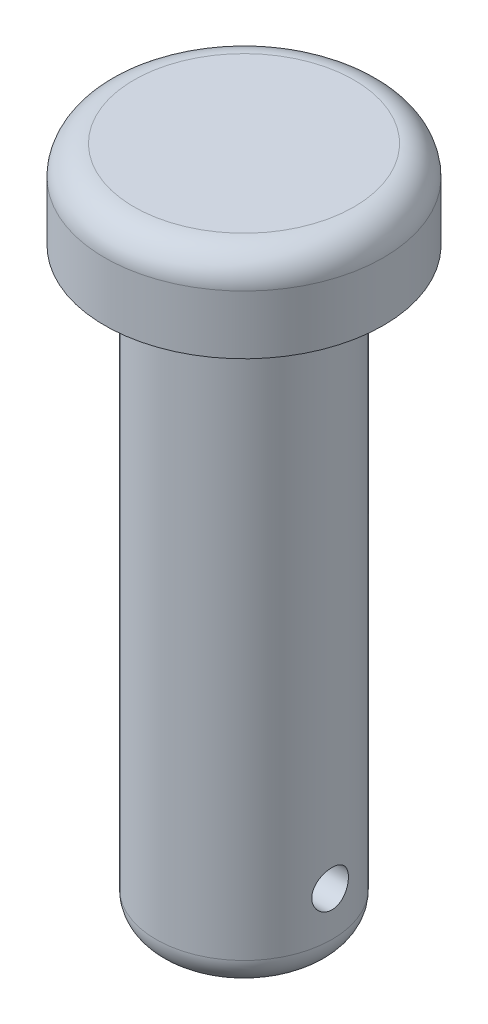
SolidWorks part; units mm, degrees
material "Alloy Steel (SS)"
ref_plane "Front Plane" through (0, 0, 0) normal (0, 0, 1) x (1, 0, 0)
ref_plane "Top Plane" through (0, 0, 0) normal (0, 1, 0) x (1, 0, 0)
ref_plane "Right Plane" through (0, 0, 0) normal (1, 0, 0) x (0, 0, -1)
sketch "Sketch1" plane through (0, 0, 0) normal (0, 0, 1) x (1, 0, 0)
  line L0 (0, -790.6523) -> (0, 38741.9609) construction
  line L1 (0, 0) -> (8, 0)
  line L2 (12, 4) -> (12, 80)
  line L3 (12, 80) -> (19, 80)
  line L4 (19, 80) -> (19, 88)
  line L5 (15, 92) -> (0, 92)
  line L6 (0, 92) -> (0, 0)
  arc A0 (8, 0) -> (12, 4) centre (8, 4) ccw
  arc A1 (19, 88) -> (15, 92) centre (15, 88) ccw
  point P11 (12, 0)
  point P14 (19, 92)
  dimension "D5" = 4
  dimension "D1" = 12
  dimension "D2" = 80
  dimension "D3" = 12
  dimension "D4" = 19
revolve "Revolve1" add sketch "Sketch1" angle 360 about L0
sketch "Sketch2" plane through (0, 0, 0) normal (1, 0, 0) x (0, 0, -1)
  line L0 (0, -1000) -> (0, 49000) construction
  circle A0 centre (0, 10) radius 2.5
  dimension "D1" = 10
  dimension "D2" = 5
extrude "Cut-Extrude1" cut sketch "Sketch2" against normal through all both and the other way through all
